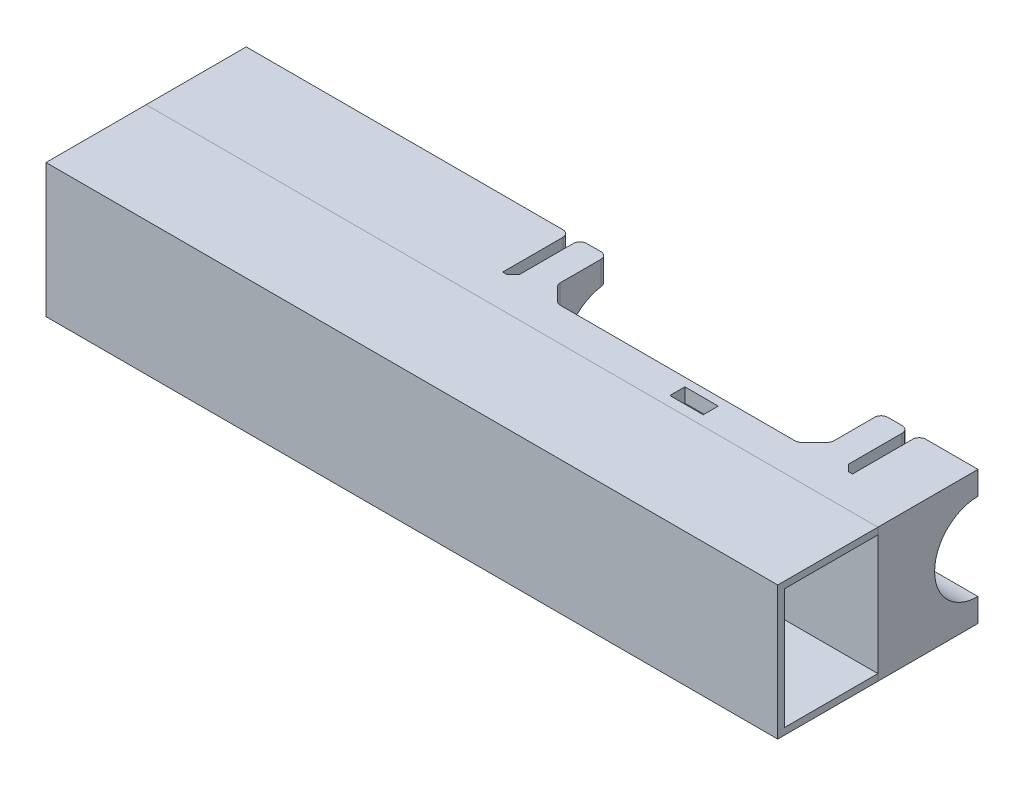
SolidWorks part; units mm, degrees
material "ABS"
ref_plane "Front Plane" through (0, 0, 0) normal (0, 0, 1) x (1, 0, 0)
ref_plane "Top Plane" through (0, 0, 0) normal (0, 1, 0) x (1, 0, 0)
ref_plane "Right Plane" through (0, 0, 0) normal (1, 0, 0) x (0, 0, -1)
sketch "Sketch1" plane through (0, 0, 0) normal (0, 1, 0) x (1, 0, 0)
  line L0 (41, 0) -> (-41, 0)
  line L1 (-41, 0) -> (-41, 20)
  line L3 (-101, 20) -> (-101, -40)
  line L9 (-41, 20) -> (-49.25, 20)
  line L10 (-49.25, 20) -> (-49.25, 0)
  line L11 (-49.25, 0) -> (-52.4, 0)
  line L12 (-52.4, 0) -> (-52.4, 20)
  line L13 (-52.4, 20) -> (-101, 20)
  line L14 (-101, -40) -> (101, -40)
  line L15 (0, -40) -> (0, 0) construction
  line L16 (52.4, 20) -> (101, 20)
  line L17 (52.4, 0) -> (52.4, 20)
  line L18 (49.25, 0) -> (52.4, 0)
  line L19 (49.25, 20) -> (49.25, 0)
  line L20 (41, 20) -> (49.25, 20)
  line L21 (101, 20) -> (101, -40)
  line L22 (41, 0) -> (41, 20)
  dimension "D1" = 41
  dimension "D2" = 40
  dimension "D3" = 3.15
  dimension "D4" = 48.6
  dimension "D5" = 60
  dimension "D6" = 60
extrude "Boss-Extrude1" add sketch "Sketch1" along normal blind 40
sketch "Sketch2" plane through (-101, 0, 0) normal (-1, 0, 0) x (0, 0, 1)
  line L0 (-20, 40) -> (-20, 0) construction
  line L1 (40, 20) -> (-7, 20) construction
  line L2 (40, 40) -> (40, 0) construction
  circle A0 centre (-20, 20) radius 13
  dimension "D1" = 47
extrude "Cut-Extrude1" cut sketch "Sketch2" against normal through all
chamfer "Chamfer1" distance 5 angle 45 2 edges at (41, 20, 0) (-41, 20, 0)
fillet "Fillet3" radius 2 16 edges at (36, 20, 0) (-36, 20, 0) (41, 20, -5) (-41, 20, -5) (-52.4, 36.5, -20) (-52.4, 3.5, -20) (-49.25, 3.5, -20) (-41, 3.5, -20) (-41, 36.5, -20) (52.4, 36.5, -20) (49.25, 36.5, -20) (49.25, 3.5, -20) (41, 3.5, -20) (41, 36.5, -20) (-49.25, 36.5, -20) (52.4, 3.5, -20)
chamfer "Chamfer2" distance 2 angle 45 2 edges at (-49.25, 20, 0) (49.25, 20, 0)
sketch "Sketch3" plane through (0, 0, -20) normal (0, 0, -1) x (-1, 0, 0)
  line L0 (56, 9.5) -> (56, 17)
  line L1 (56, 17) -> (101, 17)
  line L2 (101, 7) -> (101, 33) construction
  line L3 (101, 17) -> (101, 9.5)
  line L4 (101, 9.5) -> (56, 9.5)
  line L5 (101, 23) -> (101, 30.5)
  line L6 (101, 30.5) -> (56, 30.5)
  line L7 (56, 30.5) -> (56, 23)
  line L8 (56, 23) -> (101, 23)
  line L9 (101, 7) -> (54.4, 7) construction
  line L11 (0, 40) -> (0, -0.7286) construction
  line L12 (-35.1716, 40) -> (35.1716, 40) construction
  dimension "D1" = 45
  dimension "D2" = 7.5
  dimension "D3" = 2.5
  dimension "D4" = 2.5
extrude "Cut-Extrude2" cut sketch "Sketch3" against normal offset from surface (8.4853 mm away) 0.5
sketch "Sketch4" plane through (0, 0, 0) normal (0, 0, -1) x (-1, 0, 0)
  line L0 (0, 0) -> (0, 40) construction
  line L1 (34.1716, 35.75) -> (-34.1716, 35.75)
  line L2 (34.1716, 35.75) -> (34.1716, 4.25)
  line L3 (34.1716, 4.25) -> (-34.1716, 4.25)
  line L4 (-34.1716, 35.75) -> (-34.1716, 4.25)
  line L5 (34.1716, 35.75) -> (-34.1716, 4.25) construction
  line L6 (34.1716, 4.25) -> (-34.1716, 35.75) construction
  line L7 (-35.1716, 40) -> (35.1716, 40) construction
  line L8 (-35.1716, 0) -> (35.1716, 0) construction
  line L9 (35.1716, 0) -> (35.1716, 40) construction
  point P0 (0, 20)
  dimension "D1" = 4.25
  dimension "D2" = 1
extrude "Cut-Extrude3" cut sketch "Sketch4" against normal blind 8
sketch "Sketch5" plane through (-101, 0, 0) normal (-1, 0, 0) x (0, 0, 1)
  line L0 (-20, 7) -> (-20, 0) construction
  line L1 (-11.5147, 9.5) -> (-12.3351, 9.5) construction
  line L2 (-6.8376, 23) -> (-7.3509, 23) construction
  line L3 (-11.5147, 30.5) -> (-12.3351, 30.5) construction
  line L4 (-20, 40) -> (-20, 33) construction
  line L5 (-20, 0) -> (40, 0) construction
  line L6 (-20, 40) -> (40, 40) construction
  line L7 (40, 40) -> (40, 0) construction
  line L8 (-20, 7) -> (-20, 0)
  line L9 (-11.5147, 9.5) -> (-12.3351, 9.5)
  line L10 (-6.8376, 23) -> (-7.3509, 23)
  line L11 (-11.5147, 30.5) -> (-12.3351, 30.5)
  line L12 (-20, 40) -> (-20, 33)
  line L13 (-20, 0) -> (40, 0)
  line L14 (-20, 40) -> (40, 40)
  line L15 (40, 40) -> (40, 0)
  line L16 (-7.3509, 17) -> (-6.8376, 17)
  arc A0 (-20, 7) -> (-12.3351, 9.5) centre (-20, 20) ccw construction
  arc A1 (-12.3351, 30.5) -> (-20, 33) centre (-20, 20) ccw construction
  arc A2 (-6.8376, 23) -> (-11.5147, 30.5) centre (-20, 20) ccw construction
  arc A3 (-7.3509, 17) -> (-7.3509, 23) centre (-20, 20) ccw construction
  arc A4 (-11.5147, 9.5) -> (-6.8376, 17) centre (-20, 20) ccw construction
  arc A5 (-20, 7) -> (-12.3351, 9.5) centre (-20, 20) ccw
  arc A6 (-12.3351, 30.5) -> (-20, 33) centre (-20, 20) ccw
  arc A7 (-6.8376, 23) -> (-11.5147, 30.5) centre (-20, 20) ccw
  arc A8 (-7.3509, 17) -> (-7.3509, 23) centre (-20, 20) ccw
  arc A9 (-11.5147, 9.5) -> (-6.8376, 17) centre (-20, 20) ccw
extrude "Boss-Extrude2" add sketch "Sketch5" along normal offset from surface (48.25 mm away) 100 up to face at (-49.25, 20, -10.8333) offset beyond the face yes
sketch "Sketch6" plane through (-149.25, 0, 0) normal (-1, 0, 0) x (0, 0, 1)
  line L0 (-20, 0) -> (-20, 7) construction
  line L1 (10, 2) -> (38, 2)
  line L2 (10, 2) -> (10, 38)
  line L3 (10, 38) -> (38, 38)
  line L4 (38, 2) -> (38, 38)
  line L5 (40, 0) -> (-20, 0) construction
  line L6 (-20, 40) -> (40, 40) construction
  line L7 (40, 40) -> (40, 0) construction
  dimension "D1" = 30
  dimension "D2" = 2
  dimension "D3" = 2
  dimension "D4" = 2
extrude "Cut-Extrude4" cut sketch "Sketch6" against normal through all
sketch "Sketch7" plane through (0, 40, 0) normal (0, 1, 0) x (1, 0, 0)
  line L5 (4.6716, -2.5) -> (14.6716, -2.5)
  line L6 (4.6716, -2.5) -> (4.6716, -7)
  line L7 (4.6716, -7) -> (14.6716, -7)
  line L8 (14.6716, -2.5) -> (14.6716, -7)
  line L13 (35.1716, 0) -> (-35.1716, 0) construction
  dimension "D1" = 2.5
  dimension "D2" = 10
  dimension "D3" = 20.5
  dimension "D4" = 4.5
extrude "Cut-Extrude5" cut sketch "Sketch7" against normal up to next
sketch "Sketch9" plane through (0, 0, 10) normal (0, 0, 1) x (1, 0, 0)
  line L0 (-25.7284, 11.35) -> (-25.7284, 4.25)
  line L1 (-25.7284, 4.25) -> (27.2716, 4.25)
  line L2 (27.2716, 4.25) -> (27.2716, 16.35)
  line L3 (27.2716, 16.35) -> (20.1716, 16.35)
  line L4 (20.1716, 16.35) -> (20.1716, 11.35)
  line L5 (20.1716, 11.35) -> (-25.7284, 11.35)
  line L6 (-24.7284, 10.35) -> (-24.7284, 5.25)
  line L7 (21.1716, 10.35) -> (-24.7284, 10.35)
  line L8 (21.1716, 15.35) -> (21.1716, 10.35)
  line L9 (26.2716, 15.35) -> (21.1716, 15.35)
  line L10 (26.2716, 5.25) -> (26.2716, 15.35)
  line L11 (-24.7284, 5.25) -> (26.2716, 5.25)
  line L12 (-24.7284, 10.35) -> (-24.7284, 5.25) construction
  line L13 (21.1716, 10.35) -> (-24.7284, 10.35) construction
  line L14 (21.1716, 15.35) -> (21.1716, 10.35)
  line L15 (26.2716, 15.35) -> (21.1716, 15.35) construction
  line L16 (26.2716, 5.25) -> (26.2716, 15.35) construction
  line L17 (-24.7284, 5.25) -> (26.2716, 5.25) construction
  circle A1 centre (29.7966, 8.025) radius 1.325
  circle A2 centre (29.7966, 8.025) radius 1.325
  circle A3 centre (29.7966, 31.075) radius 1.325
  circle A4 centre (29.7966, 31.075) radius 1.325
  circle A5 centre (-28.2534, 8.025) radius 1.325
  circle A6 centre (-28.2534, 8.025) radius 1.325
  circle A7 centre (-28.2534, 31.075) radius 1.325
  circle A8 centre (-28.2534, 31.075) radius 1.325
  dimension "D1" = 0
  dimension "D2" = 1
  dimension "D3" = 0
  dimension "D4" = 0
  dimension "D6" = 0
  dimension "D7" = 0
extrude "Cut-Extrude6" cut sketch "Sketch9" against normal through all
sketch "Sketch10" plane through (0, 0, -20) normal (0, 0, -1) x (-1, 0, 0)
  line L0 (-101, 0) -> (-54.4, 0) construction
  line L1 (-101, 40) -> (-70, 40)
  line L2 (-101, 40) -> (-101, 0)
  line L3 (-101, 0) -> (-70, 0)
  line L4 (-70, 40) -> (-70, 0)
  dimension "D1" = 31
extrude "Cut-Extrude7" cut sketch "Sketch10" against normal through all
ref_plane "Plane1" through (0, 0, 10) normal (0, 0, 1) x (1, 0, 0)
split "Split1" trim tools "Plane1" bodies to split 110 resulting bodies 111 112
